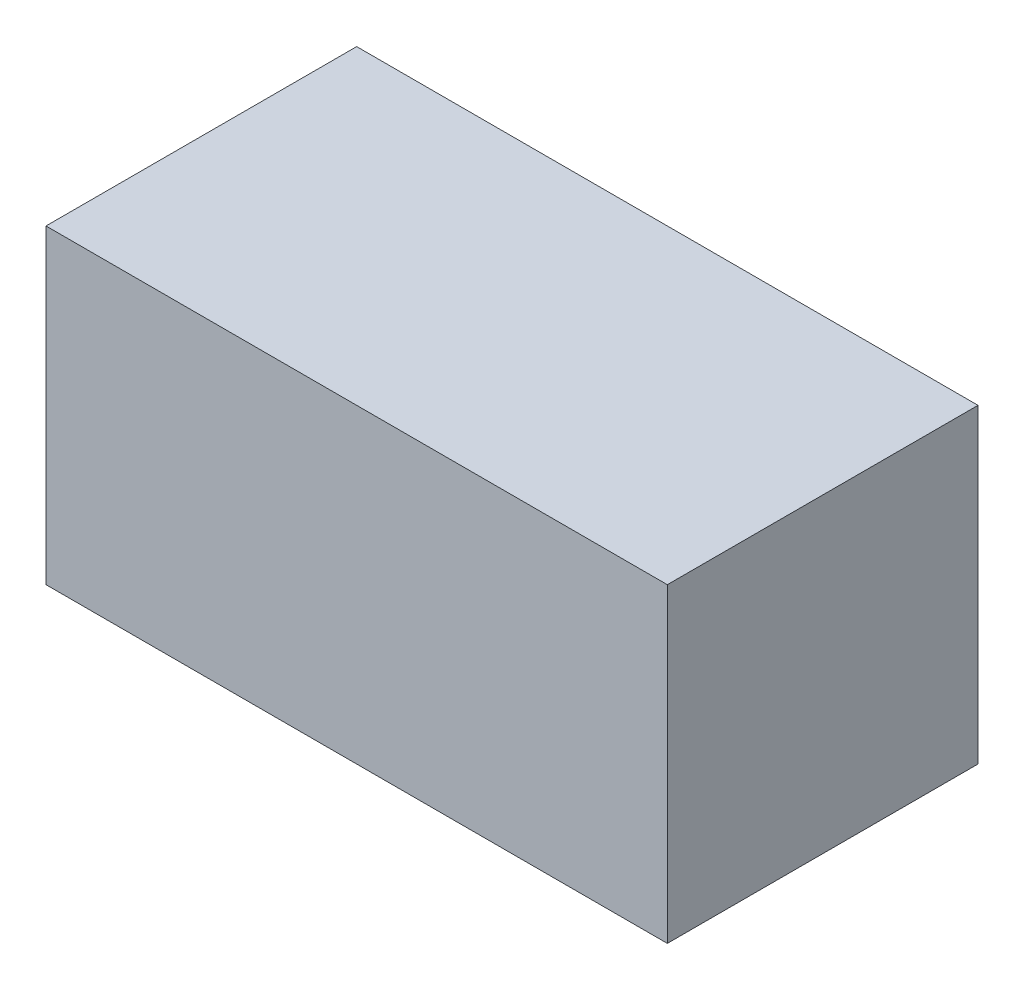
SolidWorks part; units mm, degrees
ref_plane "Płaszczyzna przednia" through (0, 0, 0) normal (0, 0, 1) x (1, 0, 0)
ref_plane "Płaszczyzna górna" through (0, 0, 0) normal (0, 1, 0) x (1, 0, 0)
ref_plane "Płaszczyzna prawa" through (0, 0, 0) normal (1, 0, 0) x (0, 0, -1)
sketch "Szkic1" plane through (0, 0, 0) normal (0, 0, 1) x (1, 0, 0)
  line L1 (-10, -5) -> (10, -5)
  line L2 (-10, -5) -> (-10, 5)
  line L3 (-10, 5) -> (10, 5)
  line L4 (10, -5) -> (10, 5)
  line L5 (-10, -5) -> (10, 5) construction
  line L6 (-10, 5) -> (10, -5) construction
  point P0 (0, 0)
  dimension "D1" = 20
  dimension "D2" = 10
extrude "Dodanie-wyciągnięcie1" add sketch "Szkic1" along normal blind 10
